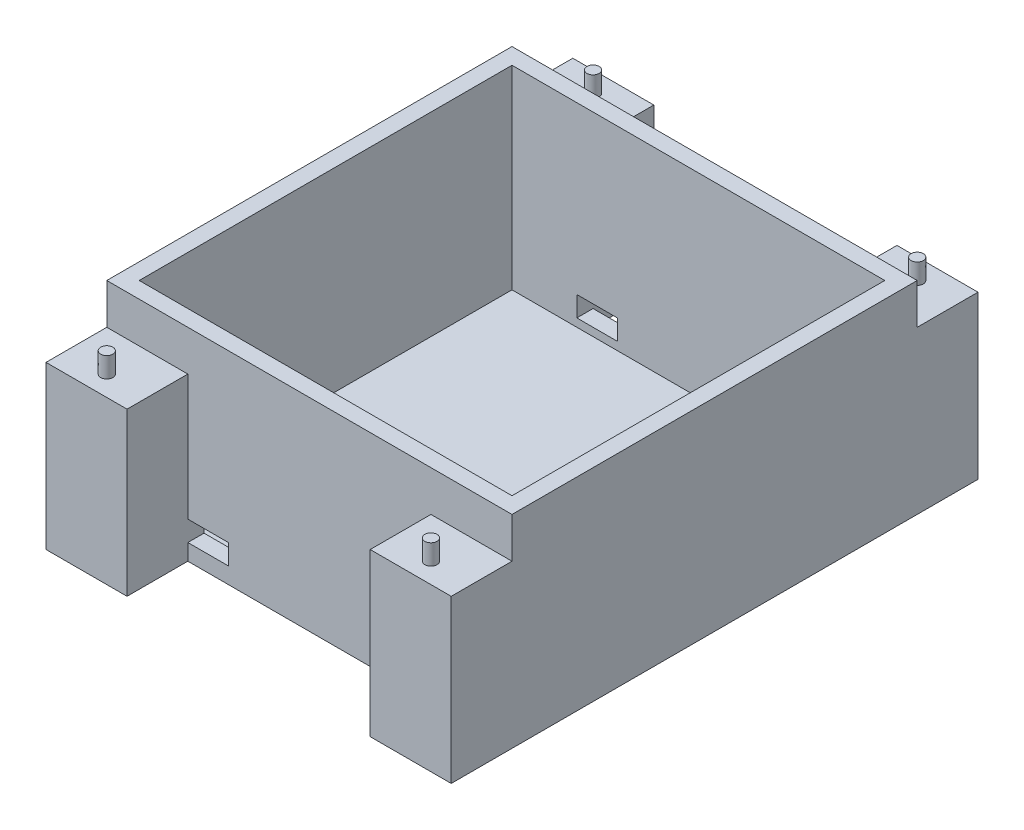
SolidWorks part; units mm, degrees
ref_plane "Front Plane" through (0, 0, 0) normal (0, 0, 1) x (1, 0, 0)
ref_plane "Top Plane" through (0, 0, 0) normal (0, 1, 0) x (1, 0, 0)
ref_plane "Right Plane" through (0, 0, 0) normal (1, 0, 0) x (0, 0, -1)
sketch "Sketch1" plane through (0, 0, 0) normal (0, 1, 0) x (1, 0, 0)
  line L1 (50, -50) -> (-50, -50)
  line L2 (50, -50) -> (50, 50)
  line L3 (50, 50) -> (-50, 50)
  line L4 (-50, -50) -> (-50, 50)
  line L5 (50, -50) -> (-50, 50) construction
  line L6 (50, 50) -> (-50, -50) construction
  point P0 (0, 0)
  dimension "D1" = 100
  dimension "D2" = 100
extrude "Boss-Extrude1" add sketch "Sketch1" along normal blind 50
sketch "Sketch2" plane through (0, 50, 0) normal (0, 1, 0) x (1, 0, 0)
  line L1 (46, -46) -> (-46, -46)
  line L2 (46, -46) -> (46, 46)
  line L3 (46, 46) -> (-46, 46)
  line L4 (-46, -46) -> (-46, 46)
  line L5 (46, -46) -> (-46, 46) construction
  line L6 (46, 46) -> (-46, -46) construction
  point P0 (0, 0)
  dimension "D1" = 92
  dimension "D2" = 92
extrude "Cut-Extrude1" cut sketch "Sketch2" against normal blind 48
sketch "Sketch6" plane through (0, 0, 50) normal (0, 0, 1) x (1, 0, 0)
  line L0 (-50, 0) -> (50, 0) construction
  line L1 (-30, 4) -> (-20, 4)
  line L2 (-30, 4) -> (-30, 9)
  line L3 (-30, 9) -> (-20, 9)
  line L4 (-20, 4) -> (-20, 9)
  line L5 (-30, 4) -> (-20, 9) construction
  line L6 (-30, 9) -> (-20, 4) construction
  line L7 (0, 50) -> (0, 0) construction
  line L8 (-50, 50) -> (50, 50) construction
  line L9 (20, 4) -> (20, 9)
  line L10 (30, 4) -> (20, 4)
  line L11 (30, 4) -> (30, 9)
  line L12 (30, 9) -> (20, 9)
  point P0 (-25, 6.5)
  dimension "D1" = 10
  dimension "D2" = 5
  dimension "D3" = 4
  dimension "D4" = 20
extrude "Cut-Extrude2" cut sketch "Sketch6" against normal through all both and the other way through all
sketch "Sketch3" plane through (0, 0, 50) normal (0, 0, 1) x (1, 0, 0)
  line L0 (-50, 50) -> (-50, 0) construction
  line L1 (-30, 40) -> (-50, 40)
  line L2 (-30, 40) -> (-30, 0)
  line L3 (-30, 0) -> (-50, 0)
  line L4 (-50, 40) -> (-50, 0)
  line L5 (-30, 40) -> (-50, 0) construction
  line L6 (-30, 0) -> (-50, 40) construction
  line L7 (-50, 0) -> (50, 0) construction
  point P0 (-40, 20)
  dimension "D1" = 20
  dimension "D2" = 40
extrude "Boss-Extrude2" add sketch "Sketch3" along normal blind 15
sketch "Sketch5" plane through (0, 40, 0) normal (0, 1, 0) x (1, 0, 0)
  line L0 (-50, -65) -> (-50, -50) construction
  line L1 (-30, -65) -> (-50, -65) construction
  circle A0 centre (-40, -60) radius 1.5
  dimension "D1" = 10
  dimension "D3" = 3
  dimension "D2" = 5
extrude "Boss-Extrude3" add sketch "Sketch5" along normal blind 5 and the other way blind 43
sketch "Sketch7" plane through (0, 0, 50) normal (0, 0, 1) x (1, 0, 0)
  line L0 (0, 50) -> (0, 0) construction
  line L1 (-50, 50) -> (50, 50) construction
ref_plane "Plane1" through (0, 0, 0) normal (-1, 0, 0) x (0, -1, 0)
mirror "Mirror1" about plane through (0, 0, 0) normal (-1, 0, 0) of "Boss-Extrude2", "Boss-Extrude3"
sketch "Sketch8" plane through (0, 0, 0) normal (0, -1, 0) x (1, 0, 0)
  line L1 (-50, -50) -> (-50, 65) construction
  line L2 (50, 65) -> (50, -50) construction
  line L4 (-50, 0) -> (50, 0)
  line L5 (50, -50) -> (-50, -50) construction
  dimension "D1" = 50
ref_plane "Plane3" through (0, 0, 0) normal (0, 0, -1) x (1, 0, 0)
mirror "Mirror2" about plane through (0, 0, 0) normal (0, 0, -1) of "Mirror1", "Boss-Extrude2", "Boss-Extrude3"
